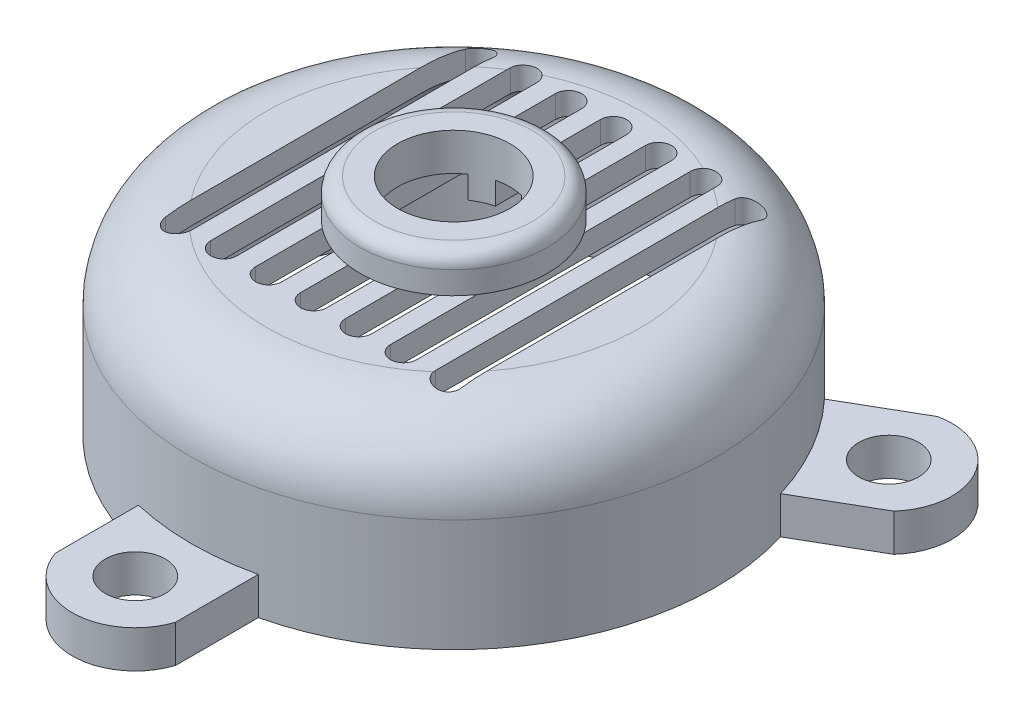
SolidWorks part; units mm, degrees
ref_plane "Front Plane" through (0, 0, 0) normal (0, 0, 1) x (1, 0, 0)
ref_plane "Top Plane" through (0, 0, 0) normal (0, 1, 0) x (1, 0, 0)
ref_plane "Right Plane" through (0, 0, 0) normal (1, 0, 0) x (0, 0, -1)
sketch "Sketch1" plane through (0, 0, 0) normal (0, 1, 0) x (1, 0, 0)
  line L0 (-137.6903, 0) -> (132.0473, 0) construction
  line L1 (0, 82.5295) -> (0, -91.2763) construction
  circle A0 centre (0, 0) radius 35
  dimension "D1" = 70
extrude "Boss-Extrude1" add sketch "Sketch1" along normal blind 25
fillet "Fillet1" radius 10 1 edges at (0, 25, 35)
shell "Shell1" thickness 3
sketch "Sketch3" plane through (0, 0, 0) normal (0, 1, 0) x (1, 0, 0)
  line L0 (0, -48.313) -> (0, 54.8287) construction
  line L1 (-59.7501, 0) -> (80.822, 0) construction
  line L2 (-20.1587, -42.5) -> (20.6952, -42.5) construction
  line L4 (-8, -45.147) -> (-8, -34.0735)
  line L5 (-8, -34.0735) -> (8, -34.0735)
  line L6 (8, -45.147) -> (8, -34.0735)
  line L7 (-8, -50.9265) -> (8, -34.0735) construction
  line L8 (-8, -34.0735) -> (8, -50.9265) construction
  circle A0 centre (0, 0) radius 35 construction
  arc A3 (-8, -45.147) -> (8, -45.147) centre (0, -42.5) ccw
  point P5 (0, -42.5)
  dimension "D1" = 16
  dimension "D2" = 42.5
extrude "Boss-Extrude2" add sketch "Sketch3" along normal blind 5
sketch "Sketch4" plane through (0, 0, 0) normal (0, -1, 0) x (1, 0, 0)
  circle A0 centre (0, 42.5) radius 4
  dimension "D2" = 8
  dimension "D1" = 42.5
extrude "Cut-Extrude1" cut sketch "Sketch4" against normal blind 5
pattern_circular "CirPattern1" count 3 over 360 about axis through (0, 0, 0) along (0, 1, 0) of "Boss-Extrude2", "Cut-Extrude1"
sketch "Sketch5" plane through (0, 25, 0) normal (0, 1, 0) x (1, 0, 0)
  circle A0 centre (0, 0) radius 7.5
  dimension "D1" = 15
extrude "Cut-Extrude2" cut sketch "Sketch5" against normal mid plane 50
sketch "Sketch6" plane through (0, 25, 0) normal (0, 1, 0) x (1, 0, 0)
  circle A0 centre (0, 0) radius 12.5
  dimension "D1" = 25
extrude "Boss-Extrude3" add sketch "Sketch6" along normal blind 5
fillet "Fillet2" radius 2 1 edges at (0, 30, 12.5)
sketch "Sketch7" plane through (0, 30, 0) normal (0, 1, 0) x (1, 0, 0)
  circle A0 centre (0, 0) radius 7.5
  dimension "D1" = 15
extrude "Cut-Extrude3" cut sketch "Sketch7" against normal blind 5
ref_plane "Plane1" through (0, 25, 0) normal (0, 1, 0) x (1, 0, 0)
sketch "Sketch8" plane through (0, 25, 0) normal (0, 1, 0) x (1, 0, 0)
  line L0 (0, -18.6877) -> (0, 21.3123) construction
  line L1 (-1.75, -18.6877) -> (-1.75, 21.3123)
  line L2 (1.75, -18.6877) -> (1.75, 21.3123)
  line L3 (7.75, -18.6877) -> (7.75, 21.3123)
  line L4 (4.25, -18.6877) -> (4.25, 21.3123)
  line L5 (6, -18.6877) -> (6, 21.3123) construction
  line L6 (13.75, -18.6877) -> (13.75, 21.3123)
  line L7 (10.25, -18.6877) -> (10.25, 21.3123)
  line L8 (12, -18.6877) -> (12, 21.3123) construction
  line L9 (19.75, -18.6877) -> (19.75, 21.3123)
  line L10 (16.25, -18.6877) -> (16.25, 21.3123)
  line L11 (18, -18.6877) -> (18, 21.3123) construction
  line L12 (-6, -18.6877) -> (-6, 21.3123) construction
  line L13 (-7.75, -18.6877) -> (-7.75, 21.3123)
  line L14 (-4.25, -18.6877) -> (-4.25, 21.3123)
  line L15 (-12, -18.6877) -> (-12, 21.3123) construction
  line L16 (-13.75, -18.6877) -> (-13.75, 21.3123)
  line L17 (-10.25, -18.6877) -> (-10.25, 21.3123)
  line L18 (-18, -18.6877) -> (-18, 21.3123) construction
  line L19 (-19.75, -18.6877) -> (-19.75, 21.3123)
  line L20 (-16.25, -18.6877) -> (-16.25, 21.3123)
  arc A0 (-1.75, -18.6877) -> (1.75, -18.6877) centre (0, -18.6877) ccw
  arc A1 (1.75, 21.3123) -> (-1.75, 21.3123) centre (0, 21.3123) ccw
  arc A2 (4.25, -18.6877) -> (7.75, -18.6877) centre (6, -18.6877) ccw
  arc A3 (7.75, 21.3123) -> (4.25, 21.3123) centre (6, 21.3123) ccw
  arc A4 (10.25, -18.6877) -> (13.75, -18.6877) centre (12, -18.6877) ccw
  arc A5 (13.75, 21.3123) -> (10.25, 21.3123) centre (12, 21.3123) ccw
  arc A6 (16.25, -18.6877) -> (19.75, -18.6877) centre (18, -18.6877) ccw
  arc A7 (19.75, 21.3123) -> (16.25, 21.3123) centre (18, 21.3123) ccw
  arc A8 (-7.75, -18.6877) -> (-4.25, -18.6877) centre (-6, -18.6877) ccw
  arc A9 (-4.25, 21.3123) -> (-7.75, 21.3123) centre (-6, 21.3123) ccw
  arc A10 (-13.75, -18.6877) -> (-10.25, -18.6877) centre (-12, -18.6877) ccw
  arc A11 (-10.25, 21.3123) -> (-13.75, 21.3123) centre (-12, 21.3123) ccw
  arc A12 (-19.75, -18.6877) -> (-16.25, -18.6877) centre (-18, -18.6877) ccw
  arc A13 (-16.25, 21.3123) -> (-19.75, 21.3123) centre (-18, 21.3123) ccw
  point P3 (0, 1.3123)
  point P12 (6, 1.3123)
  point P19 (12, 1.3123)
  point P26 (18, 1.3123)
  point P32 (-6, 1.3123)
  point P39 (-12, 1.3123)
  point P46 (-18, 1.3123)
  dimension "D3" = 4
  dimension "D1" = 3.5
  dimension "D2" = 40
  dimension "D4" = 4
extrude "Cut-Extrude4" cut sketch "Sketch8" against normal blind 5
